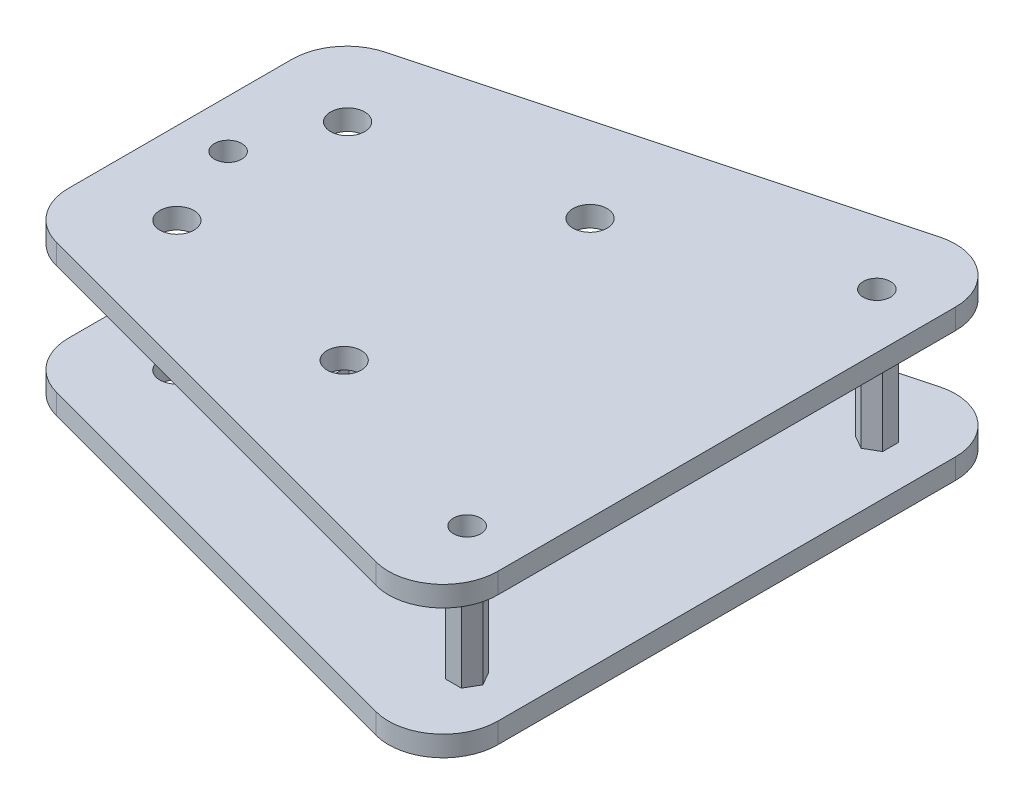
SolidWorks part; units mm, degrees
ref_plane "Alzado" through (0, 0, 0) normal (0, 0, 1) x (1, 0, 0)
ref_plane "Planta" through (0, 0, 0) normal (0, 1, 0) x (1, 0, 0)
ref_plane "Vista lateral" through (0, 0, 0) normal (1, 0, 0) x (0, 0, -1)
sketch "Croquis1" plane through (0, 0, 0) normal (0, 1, 0) x (1, 0, 0)
  line L0 (0, 16.3614) -> (0, -16.3614)
  line L1 (5.9294, -24.0888) -> (69.9294, -41.2375)
  line L2 (80, -33.5101) -> (80, 33.5101)
  line L3 (69.9294, 41.2375) -> (5.9294, 24.0888)
  line L4 (0, 0) -> (80, 0) construction
  line L5 (12, 12.5) -> (12, -12.5) construction
  line L6 (42, 18) -> (42, -18) construction
  line L7 (72, 30) -> (72, -30) construction
  circle A0 centre (12, 12.5) radius 2.5
  circle A1 centre (12, -12.5) radius 2.5
  circle A2 centre (42, 18) radius 2.5
  circle A3 centre (42, -18) radius 2.5
  arc A4 (80, 33.5101) -> (69.9294, 41.2375) centre (72, 33.5101) ccw
  arc A5 (69.9294, -41.2375) -> (80, -33.5101) centre (72, -33.5101) ccw
  arc A6 (0, -16.3614) -> (5.9294, -24.0888) centre (8, -16.3614) ccw
  arc A7 (0, 16.3614) -> (5.9294, 24.0888) centre (8, 16.3614) cw
  circle A8 centre (7, 0) radius 2
  circle A9 centre (72, -30) radius 2
  circle A10 centre (72, 30) radius 2
  point P3 (80, 0)
  point P10 (12, 0)
  point P15 (42, 0)
  point P18 (40, 0)
  point P25 (0, -22.5)
  point P28 (0, 22.5)
  point P35 (72, 0)
  dimension "D2" = 5
  dimension "D9" = 8
  dimension "D11" = 4
  dimension "D1" = 25
  dimension "D3" = 30
  dimension "D4" = 36
  dimension "D5" = 45
  dimension "D6" = 80
  dimension "D7" = 28
  dimension "D8" = 75
  dimension "D10" = 5
  dimension "D12" = 30
  dimension "D13" = 60
extrude "Saliente-Extruir1" add sketch "Croquis1" along normal blind 22
sketch "Croquis2" plane through (0, 0, 0) normal (0, 0, 1) x (1, 0, 0)
  line L0 (0, 22) -> (0, 0) construction
  line L1 (0, 19) -> (80, 19)
  line L2 (0, 19) -> (0, 3)
  line L3 (0, 3) -> (80, 3)
  line L4 (80, 19) -> (80, 3)
  line L5 (80, 22) -> (80, 0) construction
  point P8 (0, 11)
  dimension "D1" = 16
extrude "Cortar-Extruir1" cut sketch "Croquis2" against normal mid plane 100
sketch "Croquis3" plane through (0, 3, 0) normal (0, 1, 0) x (1, 0, 0)
  line L1 (7, -2.3094) -> (9, -1.1547)
  line L2 (9, -1.1547) -> (9, 1.1547)
  line L3 (9, 1.1547) -> (7, 2.3094)
  line L4 (7, 2.3094) -> (5, 1.1547)
  line L5 (5, 1.1547) -> (5, -1.1547)
  line L6 (5, -1.1547) -> (7, -2.3094)
  line L7 (70.8453, -32) -> (73.1547, -32)
  line L8 (73.1547, -32) -> (74.3094, -30)
  line L9 (74.3094, -30) -> (73.1547, -28)
  line L10 (73.1547, -28) -> (70.8453, -28)
  line L11 (70.8453, -28) -> (69.6906, -30)
  line L12 (69.6906, -30) -> (70.8453, -32)
  line L13 (74, 28.8453) -> (74, 31.1547)
  line L14 (74, 31.1547) -> (72, 32.3094)
  line L15 (72, 32.3094) -> (70, 31.1547)
  line L16 (70, 31.1547) -> (70, 28.8453)
  line L17 (70, 28.8453) -> (72, 27.6906)
  line L18 (72, 27.6906) -> (74, 28.8453)
  circle A0 centre (7, 0) radius 2 construction
  circle A1 centre (72, -30) radius 2 construction
  circle A2 centre (72, 30) radius 2 construction
  circle A3 centre (72, 30) radius 2 construction
  circle A4 centre (72, -30) radius 2 construction
  circle A5 centre (7, 0) radius 2 construction
extrude "Saliente-Extruir2" add sketch "Croquis3" along normal blind 16 separate body
sketch "Sketch1" plane through (0, 0, 0) normal (0, -1, 0) x (-1, 0, 0)
  text T0 "Yadkai" font "Century Schoolbook" height 7.5
extrude "Cut-Extrude1" cut sketch "Sketch1" against normal blind 11
